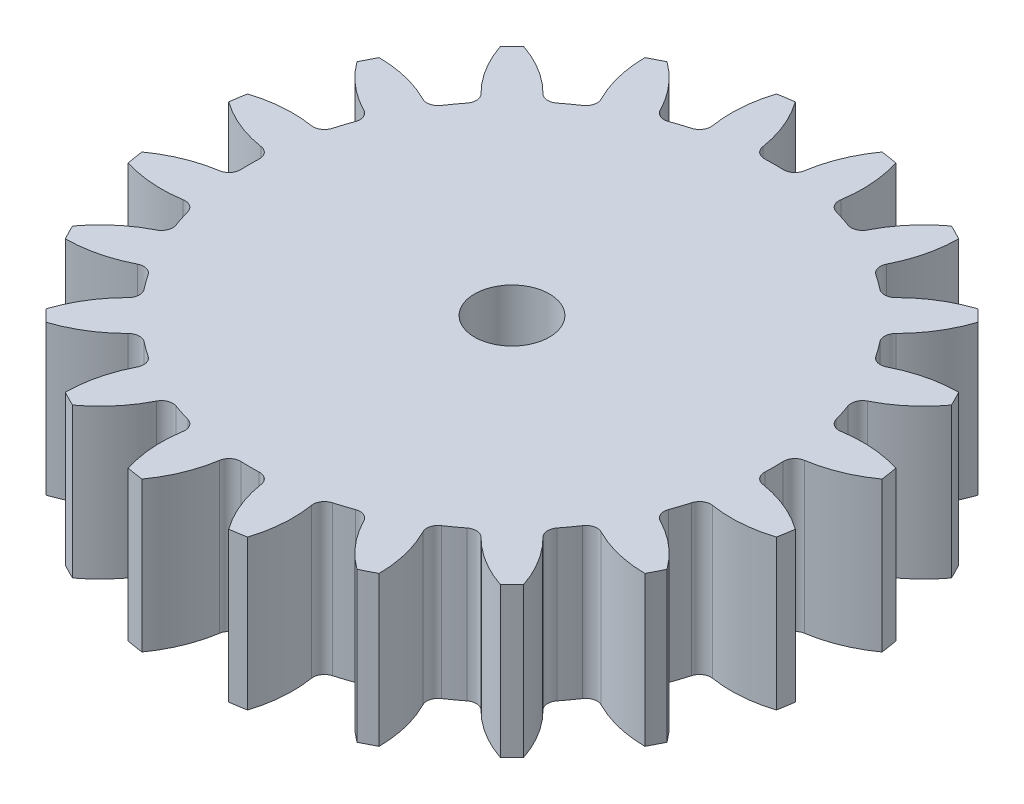
SolidWorks part; units mm, degrees
ref_plane "Front Plane" through (0, 0, 0) normal (0, 0, 1) x (1, 0, 0)
ref_plane "Top Plane" through (0, 0, 0) normal (0, 1, 0) x (1, 0, 0)
ref_plane "Right Plane" through (0, 0, 0) normal (1, 0, 0) x (0, 0, -1)
sketch "Sketch1" plane through (0, 0, 0) normal (0, 1, 0) x (1, 0, 0)
  circle A0 centre (0, 0) radius 2.5
  circle A1 centre (0, 0) radius 22
  dimension "D1" = 5
  dimension "D2" = 44
extrude "Boss-Extrude1" add sketch "Sketch1" along normal blind 10
sketch "Sketch2" plane through (0, 10, 0) normal (0, 1, 0) x (1, 0, 0)
  line L0 (0, 0) -> (0, 22) construction
  line L1 (-1.3103, 17.4509) -> (0, 0) construction
  line L2 (0, 14.786) -> (-2.5708, 21.8493) construction
  circle A0 centre (0, 0) radius 22 construction
  arc A1 (1.3103, 17.4509) -> (-1.3103, 17.4509) centre (0, 0) ccw
  arc A2 (1.8681, 19.9126) -> (-1.8681, 19.9126) centre (0, 0) ccw construction
  arc A3 (2.8963, 21.8085) -> (-2.8963, 21.8085) centre (0, 0) ccw
  arc A4 (-2.8963, 21.8085) -> (-1.3103, 17.4509) centre (-9.8515, 16.8096) cw
  arc A5 (2.8963, 21.8085) -> (1.3103, 17.4509) centre (9.8515, 16.8096) ccw
  point P16 (-1.8028, 19.7391)
  dimension "D1" = 44
  dimension "D2" = 40
  dimension "D3" = 4.5
  dimension "D4" = 20
  dimension "D5" = 3.7416
extrude "Cut-Extrude1" cut sketch "Sketch2" against normal through all
fillet "Fillet1" radius 0.76 2 edges at (1.3103, 5, -17.4509) (-1.3103, 5, -17.4509)
pattern_circular "CirPattern2" count 20 over 360 about axis through (0, 0, 0) along (0, 1, 0) of "Cut-Extrude1", "Fillet1"
sketch "Sketch3" plane through (0, 10, 0) normal (0, 1, 0) x (1, 0, 0)
  circle A0 centre (0, 0) radius 20 construction
  dimension "D1" = 40
equation "\"Module\"= 2"
equation "\"No. of Teeth\"= 20"
equation "\"Bore Diameter\"= 5"
equation "\"Pressure Angle\"= 20deg"
equation "\"Outer Diameter\"= ( \"No. of Teeth\" + 2 ) * \"Module\""
equation "\"Pitch Diameter\"= \"No. of Teeth\" * \"Module\""
equation "\"Backlash\"= 0.3 * \"Module\""
equation "\"Arc Length\"= ( \"Module\" * pi ) / 2 + \"Backlash\""
equation "\"Fillet Radius\"= .38 * \"Module\""
equation "\"Tooth Depth\"= IIF ( \"Module\" <= 1.25 , 2.4 * \"Module\" , 2.25 * \"Module\" )"
equation "\"D1@Sketch1\"=\"Bore Diameter\""
equation "\"D2@Sketch1\"=\"Outer Diameter\""
equation "\"D2@Sketch2\"=\"Pitch Diameter\""
equation "\"D1@Sketch2\"=\"Outer Diameter\""
equation "\"D3@Sketch2\"=\"Tooth Depth\""
equation "\"D4@Sketch2\"=\"Pressure Angle\""
equation "\"D5@Sketch2\"=\"Arc Length\""
equation "\"D1@Fillet1\"=\"Fillet Radius\""
equation "\"D1@CirPattern2\"=\"No. of Teeth\""
equation "\"D1@Sketch3\"=\"Pitch Diameter\""
